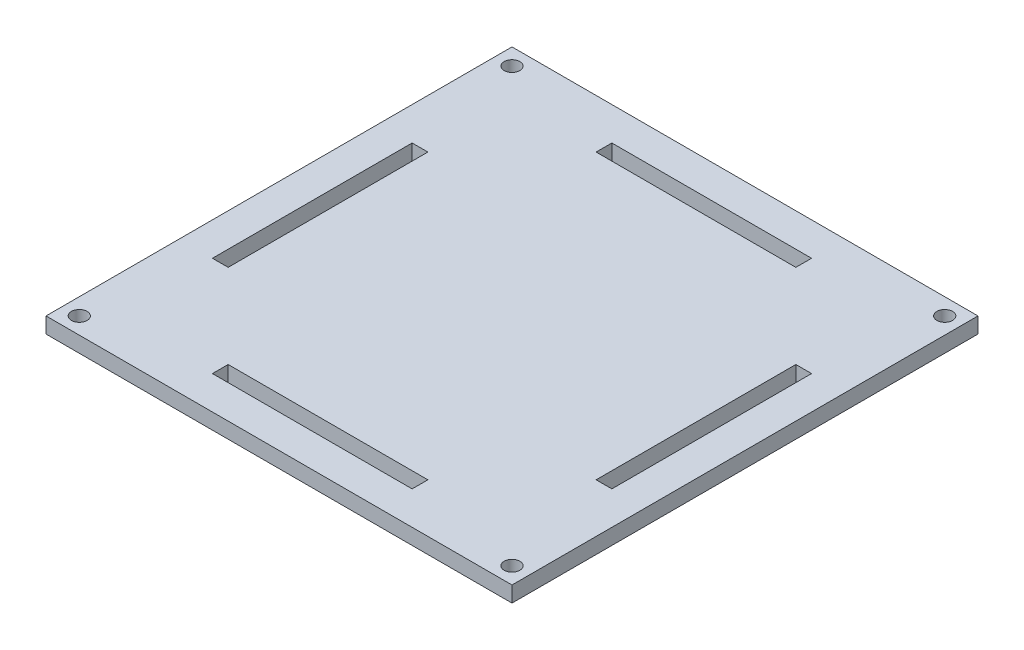
SolidWorks part; units mm, degrees
material "Acrylic (Medium-high impact)"
ref_plane "Front Plane" through (0, 0, 0) normal (0, 0, 1) x (1, 0, 0)
ref_plane "Top Plane" through (0, 0, 0) normal (0, 1, 0) x (1, 0, 0)
ref_plane "Right Plane" through (0, 0, 0) normal (1, 0, 0) x (0, 0, -1)
sketch "스케치2" plane through (0, 0, 0) normal (0, 0, 1) x (1, 0, 0)
  line L0 (44.45, -1.5) -> (46.85, 0.3) construction
  line L1 (-44.45, 1.5) -> (44.45, 1.5)
  line L2 (-44.45, 1.5) -> (-44.45, -1.5)
  line L3 (-44.45, -1.5) -> (44.45, -1.5)
  line L4 (44.45, 1.5) -> (44.45, -1.5) construction
  line L5 (-44.45, 1.5) -> (44.45, -1.5) construction
  line L6 (-44.45, -1.5) -> (44.45, 1.5) construction
  line L7 (44.45, -1.5) -> (62.738, -25.884) construction
  line L8 (46.85, 0.3) -> (65.138, -24.084) construction
  line L9 (62.738, -25.884) -> (65.138, -24.084) construction
  line L10 (44.45, -1.5) -> (44.45, -25.884) construction
  line L11 (44.45, -25.884) -> (62.738, -25.884) construction
  line L12 (44.45, 1.5) -> (44.45, -1.5)
  arc A0 (44.45, 1.5) -> (46.85, 0.3) centre (44.45, -1.5) cw construction
  point P0 (0, 0)
  dimension "D1" = 3
  dimension "D2" = 88.9
  dimension "D3" = 30.48
  dimension "D4" = 3
  dimension "D5" = 27.384
extrude "보스-돌출1" add sketch "스케치2" along normal blind 88.9 contours A0 L1 L2 L3 L7 L9 L8
sketch "스케치4" plane through (0, 1.5, 0) normal (0, 1, 0) x (1, 0, 0)
  line L0 (-44.45, -88.9) -> (-44.45, 0) construction
  line L1 (-44.45, -88.9) -> (44.45, -88.9) construction
  line L2 (-44.45, -88.9) -> (-44.45, 0) construction
  line L3 (-44.45, 0) -> (44.45, 0) construction
  line L4 (44.45, -88.9) -> (44.45, 0) construction
  line L5 (-44.45, -88.9) -> (44.45, 0) construction
  line L6 (-44.45, 0) -> (44.45, -88.9) construction
  line L7 (-44.45, 0) -> (44.45, 0) construction
  line L8 (-38.1, -82.55) -> (-44.45, -88.9) construction
  line L9 (-38.1, -82.55) -> (38.1, -82.55) construction
  line L10 (-38.1, -82.55) -> (-38.1, -6.35) construction
  line L11 (-38.1, -6.35) -> (38.1, -6.35) construction
  line L12 (38.1, -82.55) -> (38.1, -6.35) construction
  line L13 (-38.1, -82.55) -> (38.1, -6.35) construction
  line L14 (-38.1, -6.35) -> (38.1, -82.55) construction
  line L15 (44.45, 0) -> (38.1, -6.35) construction
  line L16 (0, -44.45) -> (0, -81.05) construction
  line L17 (-15.875, -79.55) -> (15.875, -79.55) construction
  line L18 (-15.875, -79.55) -> (-15.875, -82.55) construction
  line L19 (-15.875, -82.55) -> (15.875, -82.55) construction
  line L20 (15.875, -79.55) -> (15.875, -82.55) construction
  line L21 (-15.875, -79.55) -> (15.875, -82.55) construction
  line L22 (-15.875, -82.55) -> (15.875, -79.55) construction
  line L23 (-35.1, -28.575) -> (-38.1, -28.575) construction
  line L24 (-35.1, -28.575) -> (-35.1, -60.325) construction
  line L25 (-35.1, -60.325) -> (-38.1, -60.325) construction
  line L26 (-38.1, -28.575) -> (-38.1, -60.325) construction
  line L27 (15.875, -9.35) -> (15.875, -6.35) construction
  line L28 (15.875, -9.35) -> (-15.875, -9.35) construction
  line L29 (-15.875, -9.35) -> (-15.875, -6.35) construction
  line L30 (15.875, -6.35) -> (-15.875, -6.35) construction
  line L31 (35.1, -60.325) -> (38.1, -60.325) construction
  line L32 (35.1, -60.325) -> (35.1, -28.575) construction
  line L33 (35.1, -28.575) -> (38.1, -28.575) construction
  line L34 (38.1, -60.325) -> (38.1, -28.575) construction
  line L35 (0, -9.35) -> (0, -44.45) construction
  line L36 (-44.45, -88.9) -> (44.45, -88.9) construction
  line L37 (0, -44.45) -> (-35.1, -44.45) construction
  line L38 (35.1, -44.45) -> (0, -44.45) construction
  line L39 (-38.1, -65.05) -> (-35.1, -65.05) construction
  line L40 (-38.1, -14.25) -> (-35.1, -14.25) construction
  line L41 (-38.1, -14.25) -> (-38.1, -23.85) construction
  line L42 (-38.1, -23.85) -> (-35.1, -23.85) construction
  line L43 (-35.1, -14.25) -> (-35.1, -23.85) construction
  line L44 (-38.1, -14.25) -> (-35.1, -23.85) construction
  line L45 (-38.1, -23.85) -> (-35.1, -14.25) construction
  line L46 (-35.1, -74.65) -> (-35.1, -65.05) construction
  line L47 (-38.1, -74.65) -> (-35.1, -74.65) construction
  line L48 (-38.1, -74.65) -> (-38.1, -65.05) construction
  line L49 (38.1, -74.65) -> (38.1, -65.05) construction
  line L50 (38.1, -74.65) -> (35.1, -74.65) construction
  line L51 (35.1, -74.65) -> (35.1, -65.05) construction
  line L52 (38.1, -65.05) -> (35.1, -65.05) construction
  line L53 (38.1, -23.85) -> (35.1, -23.85) construction
  line L54 (35.1, -14.25) -> (35.1, -23.85) construction
  line L55 (38.1, -14.25) -> (35.1, -14.25) construction
  line L56 (38.1, -14.25) -> (38.1, -23.85) construction
  line L57 (30.2, -6.35) -> (20.6, -6.35) construction
  line L58 (-30.2, -9.35) -> (-20.6, -9.35) construction
  line L59 (-30.2, -9.35) -> (-30.2, -6.35) construction
  line L60 (-30.2, -6.35) -> (-20.6, -6.35) construction
  line L61 (-20.6, -9.35) -> (-20.6, -6.35) construction
  line L62 (-30.2, -9.35) -> (-20.6, -6.35) construction
  line L63 (-30.2, -6.35) -> (-20.6, -9.35) construction
  line L64 (20.6, -9.35) -> (20.6, -6.35) construction
  line L65 (30.2, -9.35) -> (20.6, -9.35) construction
  line L66 (30.2, -9.35) -> (30.2, -6.35) construction
  line L67 (30.2, -79.55) -> (30.2, -82.55) construction
  line L68 (30.2, -79.55) -> (20.6, -79.55) construction
  line L69 (20.6, -79.55) -> (20.6, -82.55) construction
  line L70 (30.2, -82.55) -> (20.6, -82.55) construction
  line L71 (-30.2, -82.55) -> (-20.6, -82.55) construction
  line L72 (-20.6, -79.55) -> (-20.6, -82.55) construction
  line L73 (-30.2, -79.55) -> (-20.6, -79.55) construction
  line L74 (-30.2, -79.55) -> (-30.2, -82.55) construction
  line L75 (-38.04, -74.65) -> (-35.16, -74.65) construction
  line L76 (-38.04, -23.85) -> (-35.16, -23.85) construction
  line L77 (-38.04, -23.85) -> (-38.04, -14.25) construction
  line L78 (-38.04, -14.25) -> (-35.16, -14.25) construction
  line L79 (-35.16, -23.85) -> (-35.16, -14.25) construction
  line L80 (-38.04, -23.85) -> (-35.16, -14.25) construction
  line L81 (-38.04, -14.25) -> (-35.16, -23.85) construction
  line L82 (-30.2, -6.41) -> (-20.6, -6.41) construction
  line L83 (-30.2, -6.41) -> (-30.2, -9.29) construction
  line L84 (-30.2, -9.29) -> (-20.6, -9.29) construction
  line L85 (-20.6, -6.41) -> (-20.6, -9.29) construction
  line L86 (-30.2, -6.41) -> (-20.6, -9.29) construction
  line L87 (-30.2, -9.29) -> (-20.6, -6.41) construction
  line L88 (-35.16, -65.05) -> (-35.16, -74.65) construction
  line L89 (-38.04, -65.05) -> (-35.16, -65.05) construction
  line L90 (-38.04, -65.05) -> (-38.04, -74.65) construction
  line L91 (38.04, -65.05) -> (38.04, -74.65) construction
  line L92 (38.04, -65.05) -> (35.16, -65.05) construction
  line L93 (35.16, -65.05) -> (35.16, -74.65) construction
  line L94 (38.04, -74.65) -> (35.16, -74.65) construction
  line L95 (38.04, -14.25) -> (35.16, -14.25) construction
  line L96 (35.16, -23.85) -> (35.16, -14.25) construction
  line L97 (38.04, -23.85) -> (35.16, -23.85) construction
  line L98 (38.04, -23.85) -> (38.04, -14.25) construction
  line L99 (30.2, -9.29) -> (20.6, -9.29) construction
  line L100 (20.6, -6.41) -> (20.6, -9.29) construction
  line L101 (30.2, -6.41) -> (20.6, -6.41) construction
  line L102 (30.2, -6.41) -> (30.2, -9.29) construction
  line L103 (30.2, -82.49) -> (30.2, -79.61) construction
  line L104 (30.2, -82.49) -> (20.6, -82.49) construction
  line L105 (20.6, -82.49) -> (20.6, -79.61) construction
  line L106 (30.2, -79.61) -> (20.6, -79.61) construction
  line L107 (-30.2, -79.61) -> (-20.6, -79.61) construction
  line L108 (-20.6, -82.49) -> (-20.6, -79.61) construction
  line L109 (-30.2, -82.49) -> (-20.6, -82.49) construction
  line L110 (-30.2, -82.49) -> (-30.2, -79.61) construction
  circle A0 centre (-41.275, -85.725) radius 1.5
  circle A1 centre (-41.275, -3.175) radius 1.5
  circle A2 centre (41.275, -3.175) radius 1.5
  circle A3 centre (41.275, -85.725) radius 1.5
  point P0 (0, -44.45)
  point P13 (0, -44.45)
  point P19 (0, -81.05)
  point P27 (0, -44.45)
  point P47 (0, -44.45)
  point P49 (-36.6, -19.05)
  point P65 (-25.4, -7.85)
  point P82 (-36.6, -19.05)
  point P87 (-25.4, -7.85)
  dimension "D3" = 3
  dimension "D1" = 76.2
  dimension "D2" = 76.2
  dimension "D5" = 3
  dimension "D6" = 31.75
  dimension "D8" = 35.1
  dimension "D7" = 88.9
  dimension "D9" = 3
  dimension "D10" = 35.1
  dimension "D11" = 35.1
  dimension "D12" = 9.6
  dimension "D13" = 25.4
  dimension "D14" = 3
  dimension "D15" = 9.6
  dimension "D16" = 3
  dimension "D17" = 25.4
  dimension "D18" = 2.88
  dimension "D19" = 2.88
  dimension "D4" = 4
extrude "컷-돌출1" cut sketch "스케치4" against normal up to surface (3 mm away) up to face at (0, -1.5, 44.45)
sketch "스케치5" plane through (0, 1.5, 0) normal (0, 1, 0) x (1, 0, 0)
  line L0 (0, 0) -> (0, -88.9) construction
  line L1 (-44.45, -88.9) -> (44.45, -88.9) construction
  line L2 (-44.45, -44.45) -> (44.45, -44.45) construction
  line L3 (-44.45, -88.9) -> (-44.45, 0) construction
  line L5 (44.45, -88.9) -> (44.45, 0) construction
  circle A0 centre (-14.4318, -30.0182) radius 15.875 construction
  circle A1 centre (-14.4318, -30.0182) radius 12.827 construction
  circle A2 centre (-14.4318, -30.0182) radius 1.56
  circle A3 centre (14.4318, -30.0182) radius 12.827 construction
  circle A4 centre (14.4318, -30.0182) radius 15.875 construction
  circle A5 centre (14.4318, -30.0182) radius 1.56
  circle A6 centre (14.4318, -58.8818) radius 12.827 construction
  circle A7 centre (14.4318, -58.8818) radius 15.875 construction
  circle A8 centre (14.4318, -58.8818) radius 1.56
  circle A9 centre (-14.4318, -58.8818) radius 12.827 construction
  circle A10 centre (-14.4318, -58.8818) radius 15.875 construction
  circle A11 centre (-14.4318, -58.8818) radius 1.56
  point P8 (0, -44.45)
  point P9 (-14.4318, -30.0182)
  point P10 (-1.6048, -30.0182)
  point P14 (-14.4318, -42.8452)
  point P34 (0, -44.45)
  dimension "D1" = 31.75
  dimension "D2" = 25.654
  dimension "D5" = 3.12
  dimension "D3" = 28.8636
  dimension "D4" = 28.8636
  dimension "D6" = 4
sketch "스케치10" plane through (0, 1.5, 0) normal (0, 1, 0) x (1, 0, 0)
  line L0 (-44.45, -44.45) -> (44.45, -44.45) construction
  line L1 (-38.1, -63.5) -> (-35.1, -63.5)
  line L2 (-38.1, -63.5) -> (-38.1, -25.4)
  line L3 (-38.1, -25.4) -> (-35.1, -25.4)
  line L4 (-35.1, -63.5) -> (-35.1, -25.4)
  line L5 (-38.1, -63.5) -> (-35.1, -25.4) construction
  line L6 (-38.1, -25.4) -> (-35.1, -63.5) construction
  line L7 (-44.45, -88.9) -> (-44.45, 0) construction
  line L8 (44.45, -88.9) -> (44.45, 0) construction
  line L9 (-19.05, -6.35) -> (19.05, -6.35)
  line L10 (-19.05, -6.35) -> (-19.05, -9.35)
  line L11 (-19.05, -9.35) -> (19.05, -9.35)
  line L12 (19.05, -6.35) -> (19.05, -9.35)
  line L13 (38.1, -25.4) -> (38.1, -63.5)
  line L14 (38.1, -25.4) -> (35.1, -25.4)
  line L15 (35.1, -25.4) -> (35.1, -63.5)
  line L16 (38.1, -63.5) -> (35.1, -63.5)
  line L17 (19.05, -82.55) -> (-19.05, -82.55)
  line L18 (19.05, -82.55) -> (19.05, -79.55)
  line L19 (19.05, -79.55) -> (-19.05, -79.55)
  line L20 (-19.05, -82.55) -> (-19.05, -79.55)
  point P0 (-36.6, -44.45)
  point P12 (0, -44.45)
  point P27 (0, -44.45)
  dimension "D1" = 3
  dimension "D2" = 38.1
  dimension "D3" = 38.1
  dimension "D4" = 4
extrude "컷-돌출6" cut sketch "스케치10" against normal up to surface (3 mm away) up to face at (41.275, -1.5, 87.225)
